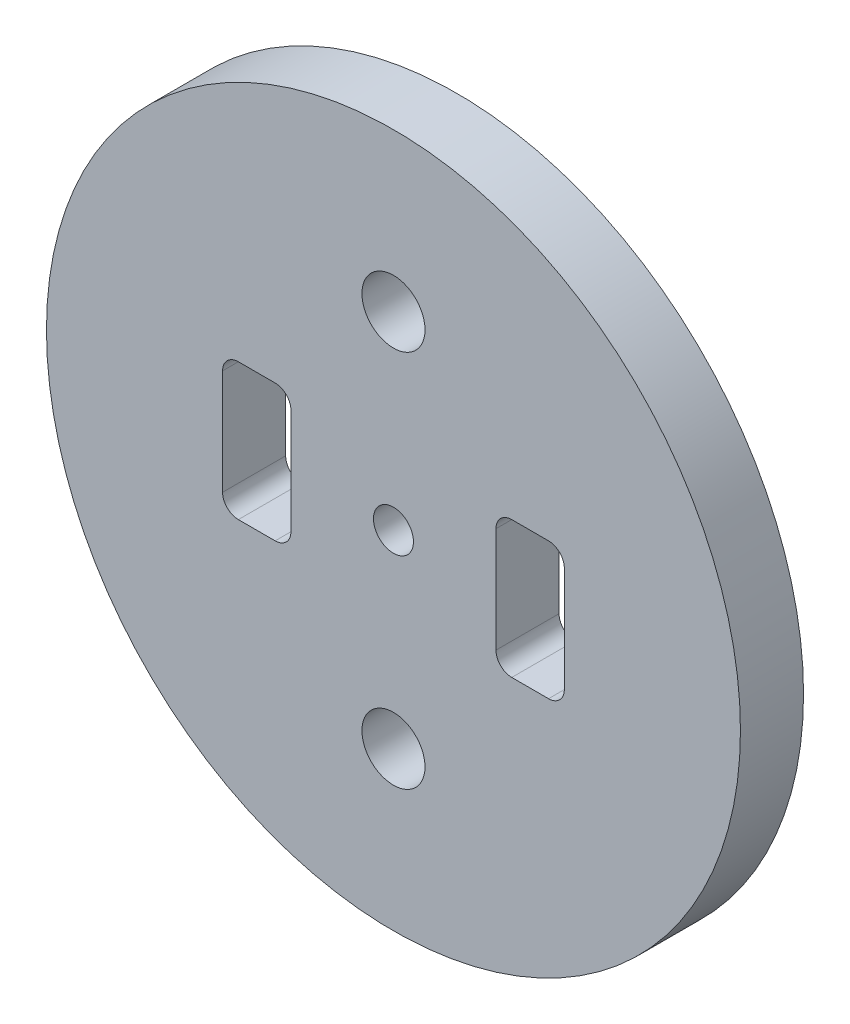
SolidWorks part; units mm, degrees
ref_plane "Alzado" through (0, 0, 0) normal (0, 0, 1) x (1, 0, 0)
ref_plane "Planta" through (0, 0, 0) normal (0, 1, 0) x (1, 0, 0)
ref_plane "Vista lateral" through (0, 0, 0) normal (1, 0, 0) x (0, 0, -1)
sketch "Model" plane through (0, 0, 0) normal (0, 0, 1) x (1, 0, 0)
  line L0 (223.1228, 245.202) -> (221.3728, 245.202)
  line L1 (223.8728, 239.452) -> (223.8728, 244.452)
  line L2 (221.3728, 238.702) -> (223.1228, 238.702)
  line L3 (220.6228, 244.452) -> (220.6228, 239.452)
  line L4 (208.3728, 245.202) -> (210.1228, 245.202)
  line L5 (207.6228, 239.452) -> (207.6228, 244.452)
  line L6 (210.1228, 238.702) -> (208.3728, 238.702)
  line L7 (210.8728, 244.452) -> (210.8728, 239.452)
  circle A0 centre (215.7478, 241.952) radius 0.95
  circle A1 centre (215.7478, 232.952) radius 1.5
  circle A2 centre (215.7478, 250.952) radius 1.5
  arc A3 (221.3728, 245.202) -> (220.6228, 244.452) centre (221.3728, 244.452) ccw
  arc A4 (223.8728, 244.452) -> (223.1228, 245.202) centre (223.1228, 244.452) ccw
  arc A5 (223.1228, 238.702) -> (223.8728, 239.452) centre (223.1228, 239.452) ccw
  arc A6 (220.6228, 239.452) -> (221.3728, 238.702) centre (221.3728, 239.452) ccw
  arc A7 (210.8728, 244.452) -> (210.1228, 245.202) centre (210.1228, 244.452) ccw
  arc A8 (208.3728, 245.202) -> (207.6228, 244.452) centre (208.3728, 244.452) ccw
  arc A9 (207.6228, 239.452) -> (208.3728, 238.702) centre (208.3728, 239.452) ccw
  arc A10 (210.1228, 238.702) -> (210.8728, 239.452) centre (210.1228, 239.452) ccw
  circle A11 centre (215.7478, 241.952) radius 16.5
extrude "Saliente-Extruir1" add sketch "Model" along normal blind 3
